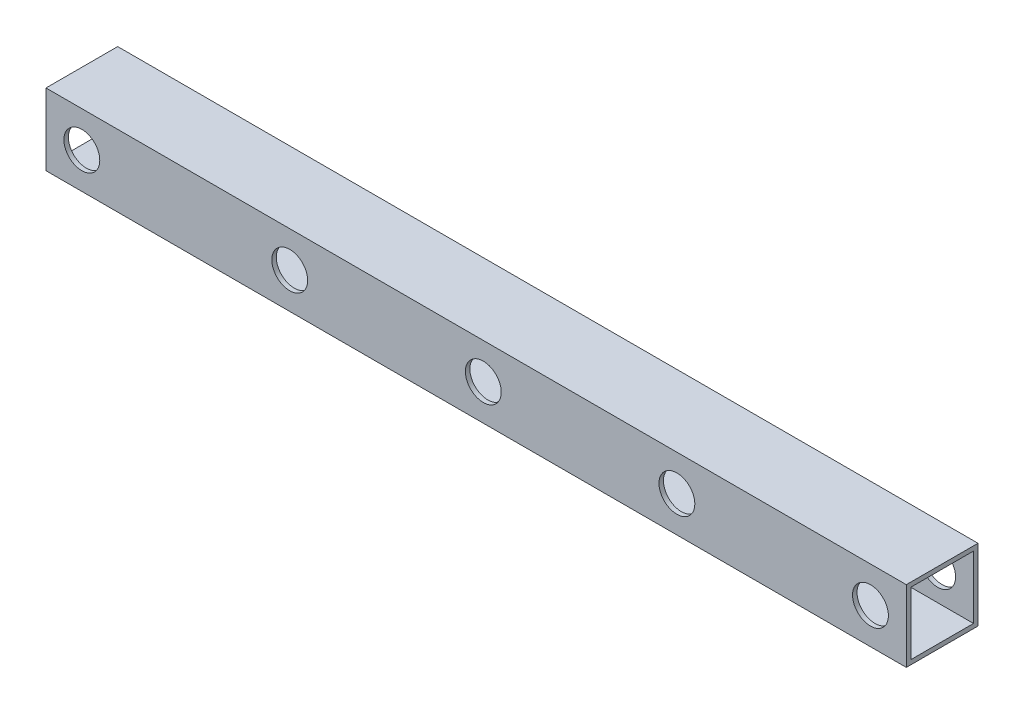
SolidWorks part; units mm, degrees
material "1060 Alloy"
ref_plane "Front Plane" through (0, 0, 0) normal (0, 0, 1) x (1, 0, 0)
ref_plane "Top Plane" through (0, 0, 0) normal (0, 1, 0) x (1, 0, 0)
ref_plane "Right Plane" through (0, 0, 0) normal (1, 0, 0) x (0, 0, -1)
sketch "Sketch1" plane through (0, 0, 0) normal (0, 1, 0) x (1, 0, 0)
  line L0 (0, 0) -> (304.8, 0)
  line L1 (304.8, 0) -> (304.8, 25.4)
  line L2 (304.8, 25.4) -> (0, 25.4)
  line L3 (0, 25.4) -> (0, 0)
extrude "Boss-Extrude1" add sketch "Sketch1" against normal blind 25.4
sketch "Sketch2" plane through (0, 0, 0) normal (-1, 0, 0) x (0, 0, 1)
  line L0 (-1.5875, -1.5875) -> (-23.8125, -1.5875)
  line L1 (-23.8125, -1.5875) -> (-23.8125, -23.8125)
  line L2 (-23.8125, -23.8125) -> (-1.5875, -23.8125)
  line L3 (-1.5875, -23.8125) -> (-1.5875, -1.5875)
extrude "Cut-Extrude1" cut sketch "Sketch2" against normal through all
hole_wizard "Hole1" positions "Sketch4" profile "Sketch3" legacy
sketch "Sketch4" plane through (0, 0, -23.8125) normal (0, 0, 1) x (1, 0, 0)
  point P0 (292.1, -12.7)
  point P1 (12.7, -12.7)
sketch "Sketch3" plane through (292.1, -12.7, -23.8125) normal (1, 0, 0) x (0, -1, 0)
  line L0 (0, 0) -> (0, 29.5275)
  line L1 (0, 29.5275) -> (6.35, 29.5275)
  line L2 (6.35, 29.5275) -> (6.35, 0)
  line L3 (6.35, 0) -> (0, 0)
  line L4 (0, 110) -> (0, -10) construction
  dimension "Diameter" = 12.7
  dimension "Depth" = 29.5275
hole_wizard "Hole2" positions "Sketch6" profile "Sketch5" legacy
sketch "Sketch6" plane through (0, 0, 0) normal (0, 0, 1) x (1, 0, 0)
  point P0 (292.1, -12.7)
  point P1 (12.7, -12.7)
sketch "Sketch5" plane through (292.1, -12.7, 0) normal (1, 0, 0) x (0, -1, 0)
  line L0 (0, 0) -> (0, 25.4)
  line L1 (0, 25.4) -> (6.35, 25.4)
  line L2 (6.35, 25.4) -> (6.35, 0)
  line L3 (6.35, 0) -> (0, 0)
  line L4 (0, 110) -> (0, -10) construction
  dimension "Diameter" = 12.7
  dimension "Depth" = 25.4
pattern_linear "LPattern1" count 2 spacing 27.94 along (0, 0, 1) count 4 spacing 68.58 along (-1, 0, 0) of "Hole1"
